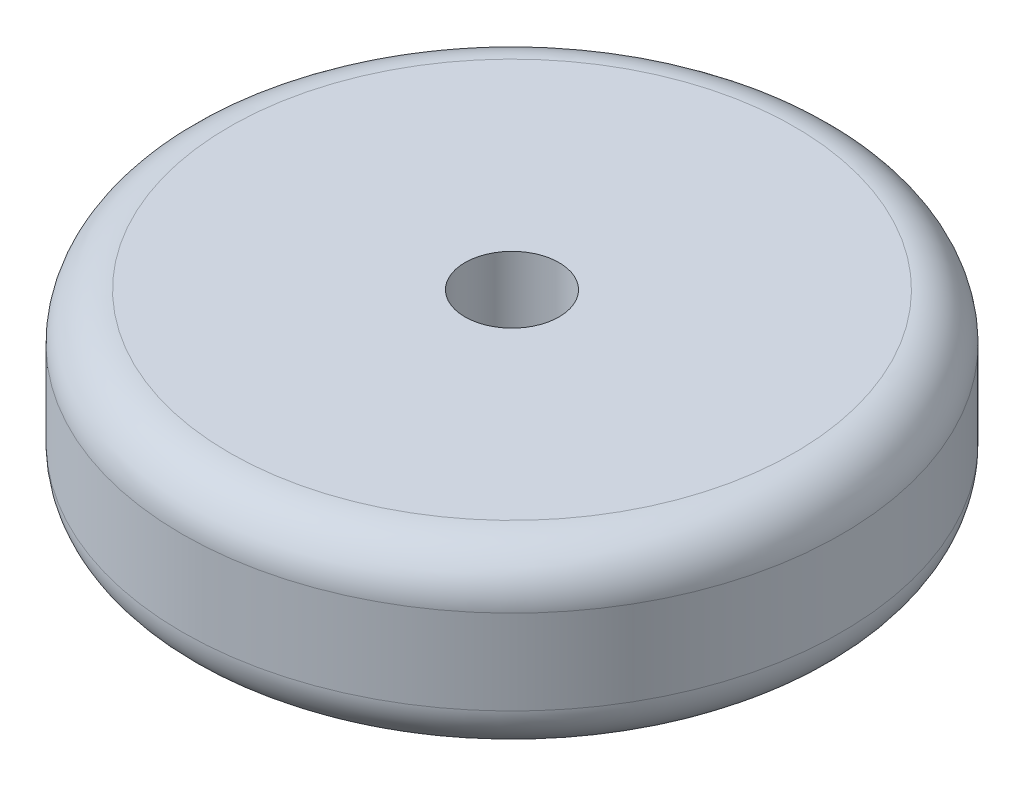
SolidWorks part; units mm, degrees
ref_plane "Plano frontal" through (0, 0, 0) normal (0, 0, 1) x (1, 0, 0)
ref_plane "Plano superior" through (0, 0, 0) normal (0, 1, 0) x (1, 0, 0)
ref_plane "Plano direito" through (0, 0, 0) normal (1, 0, 0) x (0, 0, -1)
sketch "Esboço1" plane through (0, 0, 0) normal (0, 1, 0) x (1, 0, 0)
  circle A0 centre (0, 0) radius 3.5
  dimension "D1" = 7
extrude "Ressalto-extrusão1" add sketch "Esboço1" along normal blind 1.9
sketch "Esboço2" plane through (0, 1.9, 0) normal (0, 1, 0) x (1, 0, 0)
  circle A0 centre (0, 0) radius 0.5
  dimension "D1" = 1
extrude "Corte-extrusão1" cut sketch "Esboço2" against normal blind 1.9
fillet "Filete1" radius 0.5 2 edges at (0, 1.9, 3.5) (0, 0, 3.5)
